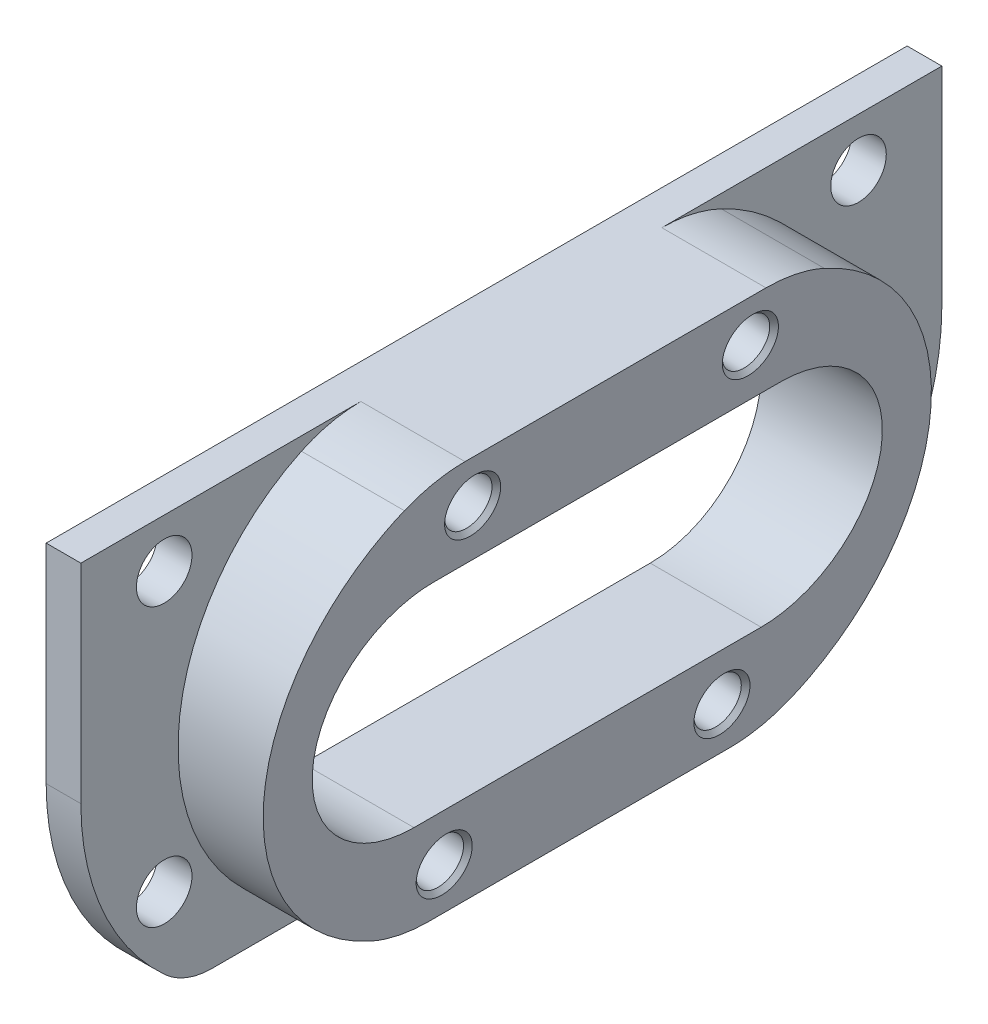
SolidWorks part; units mm, degrees
ref_plane "Płaszczyzna przednia" through (0, 0, 0) normal (0, 0, 1) x (1, 0, 0)
ref_plane "Płaszczyzna górna" through (0, 0, 0) normal (0, 1, 0) x (1, 0, 0)
ref_plane "Płaszczyzna prawa" through (0, 0, 0) normal (1, 0, 0) x (0, 0, -1)
sketch "Szkic1" plane through (0, 0, 0) normal (1, 0, 0) x (0, 0, -1)
  line L0 (-25, -16) -> (25, -16)
  line L1 (25, 16) -> (-25, 16)
  line L2 (-43.1384, -30) -> (43.1384, -30)
  line L3 (-62, 0) -> (62, 0) construction
  line L4 (-62, 30) -> (62, 30)
  line L5 (62, 0) -> (62, 30)
  line L6 (-62, 30) -> (-62, 0)
  line L7 (0, 0) -> (0, 30) construction
  arc A0 (-25, 16) -> (-25, -16) centre (-25, 0) ccw
  arc A1 (25, -16) -> (25, 16) centre (25, 0) ccw
  arc A2 (43.1384, -30) -> (49.8563, -27.4074) centre (43.1384, -20) ccw
  arc A3 (-49.8563, -27.4074) -> (-43.1384, -30) centre (-43.1384, -20) ccw
  arc A6 (49.8563, -27.4074) -> (62, 0) centre (25, 0) ccw
  arc A7 (-62, 0) -> (-49.8563, -27.4074) centre (-25, 0) ccw
  circle A8 centre (-50, 23) radius 4
  circle A9 centre (50, 23) radius 4
  circle A10 centre (50, -17) radius 4
  circle A11 centre (-50, -17) radius 4
  dimension "D2" = 16
  dimension "D3" = 10
  dimension "D4" = 7
  dimension "D5" = 37
  dimension "D10" = 8
  dimension "D1" = 50
  dimension "D6" = 43.1384
  dimension "D7" = 50
  dimension "D8" = 2
  dimension "D9" = 2
extrude "Dodanie-wyciągnięcie1" add sketch "Szkic1" along normal blind 20
sketch "Szkic2" plane through (20, 0, 0) normal (1, 0, 0) x (0, 0, -1)
  line L0 (-25, -16) -> (25, -16) construction
  line L1 (25, 16) -> (-25, 16) construction
  line L2 (-25, -16) -> (25, -16)
  line L3 (25, 16) -> (-25, 16)
  line L6 (21.6718, 30) -> (-21.6718, 30)
  line L7 (-21.6718, -30) -> (21.6718, -30)
  line L8 (0, 0) -> (0, 16) construction
  arc A0 (25, -16) -> (25, 16) centre (25, 0) ccw construction
  arc A1 (-25, 16) -> (-25, -16) centre (-25, 0) ccw construction
  arc A2 (25, -16) -> (25, 16) centre (25, 0) ccw
  arc A3 (-25, 16) -> (-25, -16) centre (-25, 0) ccw
  arc A6 (-30.2337, -28.0747) -> (-30.2337, 28.0747) centre (-16.9348, 0) cw
  arc A7 (30.2337, -28.0747) -> (30.2337, 28.0747) centre (16.9348, 0) ccw
  arc A8 (-30.2337, -28.0747) -> (-21.6718, -30) centre (-21.6718, -10) ccw
  arc A9 (21.6718, -30) -> (30.2337, -28.0747) centre (21.6718, -10) ccw
  arc A10 (30.2337, 28.0747) -> (21.6718, 30) centre (21.6718, 10) ccw
  arc A11 (-21.6718, 30) -> (-30.2337, 28.0747) centre (-21.6718, 10) ccw
  point P4 (-25, 0)
  point P5 (-25, 23)
  point P8 (-25, -23)
  point P9 (25, -23)
  point P10 (25, 0)
  point P11 (25, 23)
  point P23 (-25, -30)
  point P26 (25, -30)
  point P29 (25, 30)
  point P32 (-25, 30)
  dimension "D1" = 20
  dimension "D2" = 20
  dimension "D3" = 20
  dimension "D4" = 20
extrude "Wytnij-wyciągnięcie1" cut sketch "Szkic2" against normal blind 15 flip side to cut
sketch "Szkic3" plane through (0, 0, -62) normal (0, 0, -1) x (-1, 0, 0)
  line L4 (-5, 0) -> (-20, 0) construction
  line L5 (-20, 30) -> (-14.7507, -30)
  line L6 (-20, 30) -> (-20, -30)
  line L7 (-14.7507, -30) -> (-20, -30)
extrude "Wytnij-wyciągnięcie2" cut sketch "Szkic3" against normal through all both and the other way through all
sketch "Szkic9" plane through (17.2434, -1.5086, 0) normal (0.9962, -0.0872, 0) x (0, 0, -1)
  line L0 (9, 1.5144) -> (-41.9594, 1.5144) construction
  line L1 (0, 0) -> (0, 22.9605) construction
  line L2 (25, 17.5755) -> (-25, 17.5755)
  line L3 (-25, -14.5468) -> (25, -14.5468)
  line L4 (25, 17.5755) -> (-25, 17.5755)
  line L5 (-25, -14.5468) -> (25, -14.5468)
  line L7 (0, 0) -> (0, -18.3021) construction
  ellipse E2 centre (-25, 1.5144) end of major axis (-25, -14.5468) minor radius 16 (-25, 17.5755) -> (-25, -14.5468) ccw
  ellipse E3 centre (25, 1.5144) end of major axis (25, -14.5468) minor radius 16 (25, -14.5468) -> (25, 17.5755) ccw
  ellipse E4 centre (-25, 1.5144) end of major axis (-25, -14.5468) minor radius 16 (-25, 17.5755) -> (-25, -14.5468) ccw
  ellipse E5 centre (25, 1.5144) end of major axis (25, -14.5468) minor radius 16 (25, -14.5468) -> (25, 17.5755) ccw
  point P4 (-20, 25.0144)
  point P14 (20, 25.0144)
  point P19 (20, -21.9856)
  point P20 (-20, -21.9856)
  dimension "D2" = 23.5
  dimension "D3" = 20
  dimension "D1" = 0
  dimension "D4" = 2
  dimension "D5" = 2
hole_wizard "Otwór gwintowany M81" positions "Szkic 3D1" profile "Szkic11" tap size "M8" standard "ISO"
sketch3d "Szkic 3D1"
  point P0 (19.4235, 23.4106, 20)
  point P3 (19.4235, 23.4106, -20)
  point P6 (15.3272, -23.4106, -20)
  point P9 (15.3272, -23.4106, 20)
sketch "Szkic11" plane through (19.4235, 23.4106, 20) normal (0, 0, 1) x (0.0872, 0.9962, 0)
  line L0 (0, 0) -> (0, 15)
  line L1 (0, 15) -> (3.4, 12.9571)
  line L2 (3.4, 12.9571) -> (3.4, 0.625)
  line L3 (3.4, 0.625) -> (4.025, 0)
  line L5 (4.025, 0) -> (0, 0)
  line L6 (-3.4, 0.625) -> (-4.025, 0) construction
  line L10 (0, 15) -> (-3.4, 12.9571) construction
  line L11 (0, -6.35) -> (0, 107.95) construction
  dimension "Średnica wiertła gwintu" = 6.8
  dimension "Głębokość otworu gwintowanego" = 15
  dimension "Średnica zewnętrznego pogłębienia stożkowego" = 8.05
  dimension "Kąt zewnętrznego pogłębienia stożkowego" = 90
  dimension "Kąt wiertła" = 118
cosmetic thread "Gwint otworu1" parameters "D1"=12, "D2"=8
cosmetic thread "Gwint otworu2" parameters "D1"=12, "D2"=8
cosmetic thread "Gwint otworu3" parameters "D1"=12, "D2"=8
cosmetic thread "Gwint otworu4" parameters "D1"=12, "D2"=8
